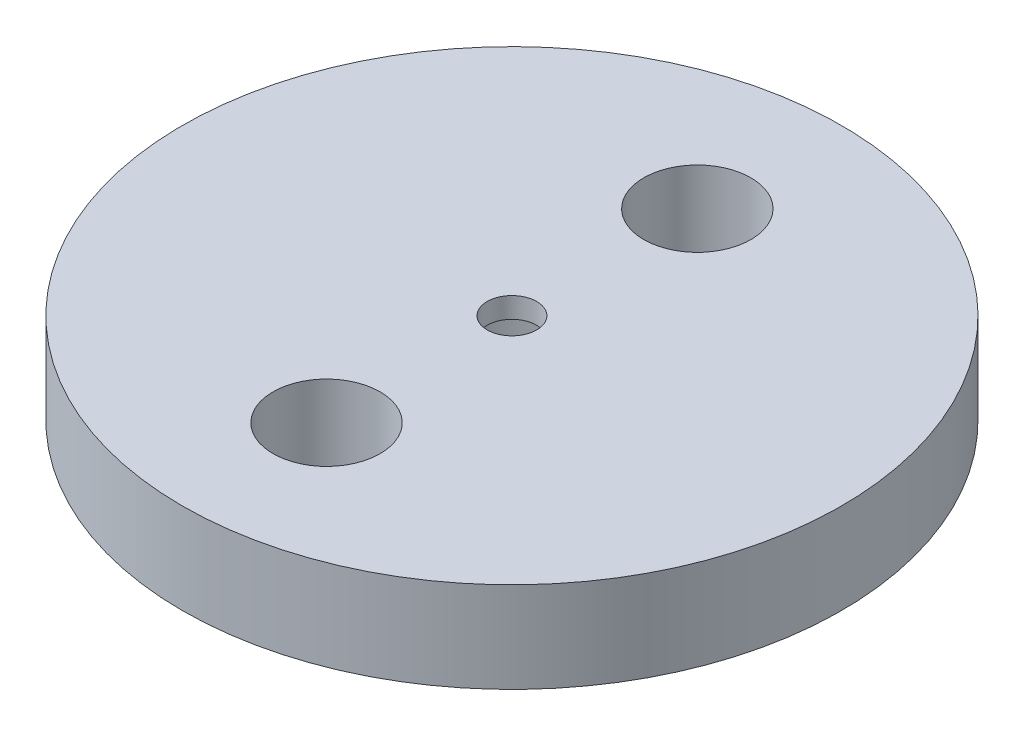
SolidWorks part; units mm, degrees
ref_plane "Front Plane" through (0, 0, 0) normal (0, 0, 1) x (1, 0, 0)
ref_plane "Top Plane" through (0, 0, 0) normal (0, 1, 0) x (1, 0, 0)
ref_plane "Right Plane" through (0, 0, 0) normal (1, 0, 0) x (0, 0, -1)
sketch "Sketch1" plane through (0, 0, 0) normal (0, 1, 0) x (1, 0, 0)
  circle A0 centre (0, 0) radius 8
  dimension "D1" = 16
extrude "Boss-Extrude1" add sketch "Sketch1" along normal blind 2.2
sketch "Sketch2" plane through (0, 2.2, 0) normal (0, 1, 0) x (1, 0, 0)
  line L0 (0, -16.0698) -> (0, 16.0698) construction
  line L1 (-27.9531, 0) -> (27.9531, 0) construction
  circle A2 centre (0, 4.5) radius 1.3
  circle A12 centre (0, -4.5) radius 1.3
  point P3 (0, 0)
  point P9 (0, 0)
  dimension "D1" = 2.6
  dimension "D2" = 4.5
extrude "Cut-Extrude1" cut sketch "Sketch2" against normal blind 2.2
sketch "Sketch3" plane through (0, 0, 0) normal (0, -1, 0) x (1, 0, 0)
  circle A0 centre (0, 0) radius 3
  circle A1 centre (0, 0) radius 2.45
  dimension "D1" = 6
  dimension "D2" = 4.9
extrude "Boss-Extrude2" add sketch "Sketch3" along normal blind 2.2
sketch "Sketch8" plane through (0, 0, 0) normal (0, -1, 0) x (1, 0, 0)
  circle A0 centre (0, 0) radius 0.6
  dimension "D1" = 1.2
extrude "Cut-Extrude7" cut sketch "Sketch8" against normal up to surface (2.2 mm away) up to face at (0, 2.2, 3.2)
sketch "Sketch9" plane through (0, 0, 0) normal (0, -1, 0) x (1, 0, 0)
  circle A0 centre (0, 0) radius 2.45
extrude "Cut-Extrude8" cut sketch "Sketch9" against normal blind 1.7
